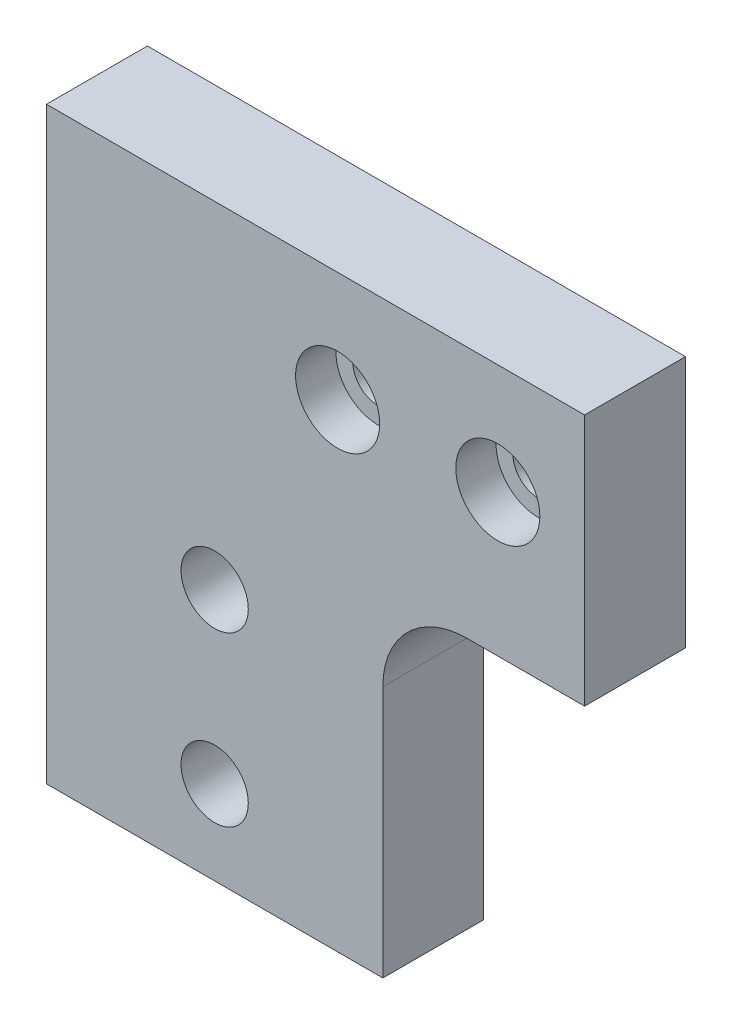
SolidWorks part; units mm, degrees
ref_plane "Plano frontal" through (0, 0, 0) normal (0, 0, 1) x (1, 0, 0)
ref_plane "Plano superior" through (0, 0, 0) normal (0, 1, 0) x (1, 0, 0)
ref_plane "Plano direito" through (0, 0, 0) normal (1, 0, 0) x (0, 0, -1)
sketch "Esboço1" plane through (0, 0, 0) normal (0, 0, 1) x (1, 0, 0)
  line L1 (-16, 17.5) -> (16, 17.5)
  line L2 (-16, 17.5) -> (-16, -17.5)
  line L3 (-16, -17.5) -> (16, -17.5)
  line L4 (16, 17.5) -> (16, -17.5)
  line L5 (-16, 17.5) -> (16, -17.5) construction
  line L6 (-16, -17.5) -> (16, 17.5) construction
  point P0 (0, 0)
  dimension "D1" = 32
  dimension "D2" = 35
extrude "Ressalto-extrusão1" add sketch "Esboço1" along normal blind 6
sketch "Esboço2" plane through (0, 0, 6) normal (0, 0, 1) x (1, 0, 0)
  line L1 (16, -17.5) -> (4, -17.5)
  line L2 (16, -17.5) -> (16, 2.5)
  line L3 (16, 2.5) -> (4, 2.5)
  line L4 (4, -17.5) -> (4, 2.5)
  line L5 (-16, -17.5) -> (16, -17.5) construction
  line L6 (-6, 17.5) -> (-6, -17.5)
  line L7 (-6, 17.5) -> (-6, -17.5) construction
  line L8 (16, 17.5) -> (-16, 17.5) construction
  circle A0 centre (-6, -12.5) radius 2
  circle A1 centre (-6, -2.5) radius 2
  dimension "D4" = 4
  dimension "D1" = 12
  dimension "D2" = 15
  dimension "D5" = 5
  dimension "D6" = 10
  dimension "D3" = 10
extrude "Corte-extrusão1" cut sketch "Esboço2" against normal up to surface (6 mm away) up to face at (0, 0, 0)
fillet "Filete1" radius 5 1 edges at (4, 2.5, 3)
sketch "Esboço5" plane through (0, 0, 0) normal (0, 0, -1) x (-1, 0, 0)
  circle A0 centre (-10.8375, 10.9375) radius 1.175 construction
  circle A1 centre (-1.3125, 10.9375) radius 1.175 construction
  circle A2 centre (-10.8375, 10.9375) radius 1.175 construction
  circle A3 centre (-1.3125, 10.9375) radius 1.175 construction
  circle A4 centre (-10.8375, 10.9375) radius 1.5
  circle A5 centre (-1.3125, 10.9375) radius 1.5
  dimension "D1" = 3
extrude "Corte-extrusão3" cut sketch "Esboço5" against normal up to surface (6 mm away) up to face at (2.2806, 0.5051, 6)
sketch "Esboço6" plane through (0, 0, 6) normal (0, 0, 1) x (1, 0, 0)
  circle A0 centre (10.8375, 10.9375) radius 2.5
  circle A1 centre (1.3125, 10.9375) radius 2.5
  dimension "D1" = 5
extrude "Corte-extrusão4" cut sketch "Esboço6" against normal blind 2.4
